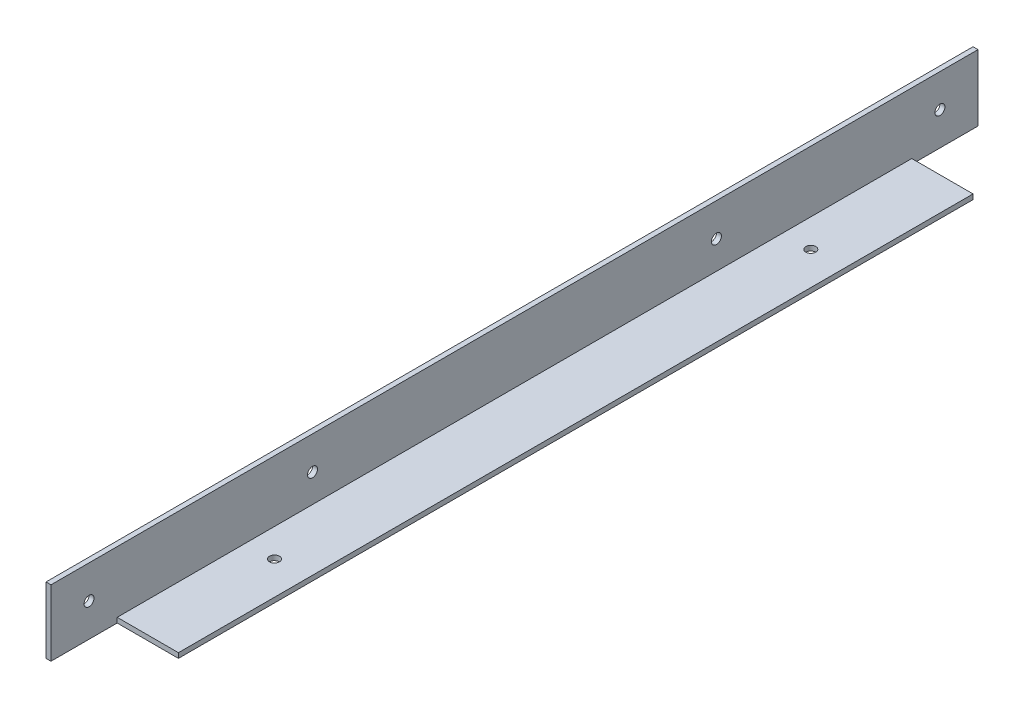
SolidWorks part; units mm, degrees
ref_plane "Plan de face" through (0, 0, 0) normal (0, 0, 1) x (1, 0, 0)
ref_plane "Plan de dessus" through (0, 0, 0) normal (0, 1, 0) x (1, 0, 0)
ref_plane "Plan de droite" through (0, 0, 0) normal (1, 0, 0) x (0, 0, -1)
sketch "Esquisse1" plane through (0, 0, 0) normal (0, 0, 1) x (1, 0, 0)
  line L0 (0, 0) -> (20, 0)
  line L1 (20, 0) -> (20, 1.5)
  line L2 (20, 1.5) -> (1.5, 1.5)
  line L3 (1.5, 1.5) -> (1.5, 20)
  line L4 (1.5, 20) -> (0, 20)
  line L5 (0, 20) -> (0, 0)
  dimension "D1" = 1.5
  dimension "D2" = 1.5
  dimension "D3" = 20
  dimension "D4" = 20
extrude "Extrusion1" add sketch "Esquisse1" along normal blind 240
sketch "Esquisse2" plane through (0, 1.5, 0) normal (0, 1, 0) x (1, 0, 0)
  line L0 (20, -240) -> (20, 0) construction
  line L1 (20, 0) -> (1.5, 0) construction
  line L2 (20, -240) -> (1.5, -240) construction
  circle A0 centre (10, -39) radius 1.5
  circle A1 centre (10, -201) radius 1.5
  point P8 (10.75, -240)
  dimension "D1" = 10
  dimension "D2" = 39
  dimension "D5" = 39
  dimension "D6" = 10
extrude "Extrusion2" cut sketch "Esquisse2" against normal through all
sketch "Esquisse3" plane through (0, 0, 240) normal (0, 0, 1) x (1, 0, 0)
  line L0 (0, 20) -> (1.5, 20)
  line L1 (1.5, 20) -> (1.5, 0)
  line L2 (0, 0) -> (20, 0) construction
  line L3 (1.5, 0) -> (0, 0)
  line L4 (0, 0) -> (0, 20)
extrude "Extrusion3" add sketch "Esquisse3" along normal blind 20
sketch "Esquisse5" plane through (0, 0, 0) normal (0, 0, -1) x (-1, 0, 0)
  line L0 (-1.5, 20) -> (0, 20)
  line L1 (0, 20) -> (0, 0)
  line L2 (0, 0) -> (-1.5, 0)
  line L3 (-1.5, 0) -> (-1.5, 20)
extrude "Extrusion4" add sketch "Esquisse5" along normal blind 20
sketch "Esquisse6" plane through (1.5, 0, 0) normal (1, 0, 0) x (0, 0, -1)
  line L0 (-260, 0) -> (-260, 20) construction
  line L1 (-260, 0) -> (-240, 0) construction
  line L2 (20, 20) -> (20, 0) construction
  circle A0 centre (-248.5, 10) radius 1.5
  circle A1 centre (8.5, 10) radius 1.5
  circle A2 centre (-181, 10) radius 1.5
  circle A3 centre (-59, 10) radius 1.5
  point P2 (-260, 10)
  dimension "D3" = 11.5
  dimension "D4" = 79
  dimension "D1" = 11.5
  dimension "D2" = 10
  dimension "D5" = 79
extrude "Extrusion5" cut sketch "Esquisse6" against normal through all
